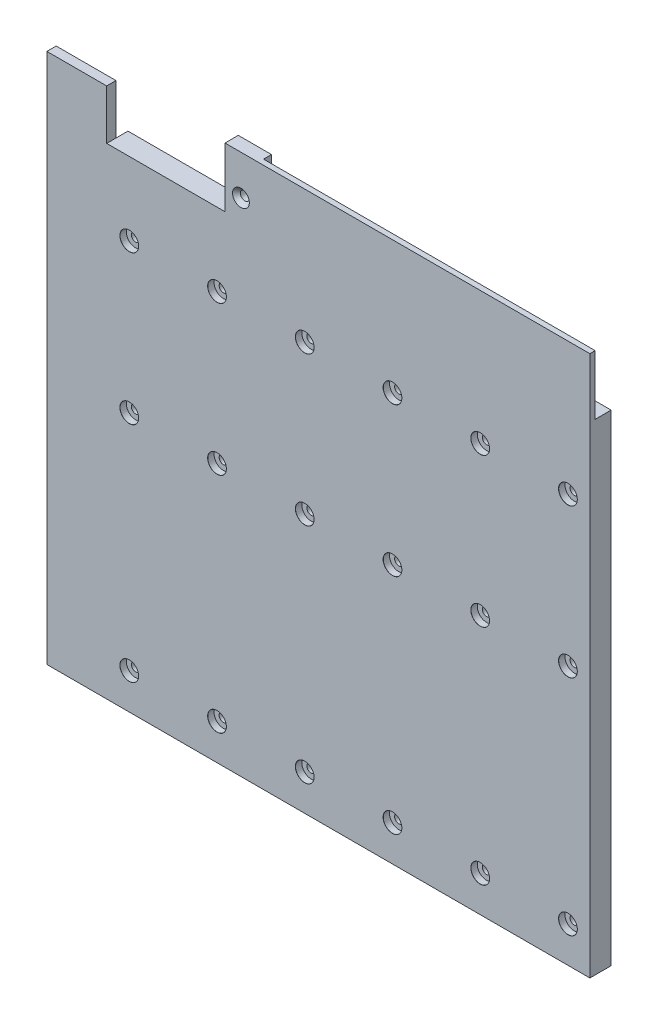
SolidWorks part; units mm, degrees
ref_plane "Plan de face" through (0, 0, 0) normal (0, 0, 1) x (1, 0, 0)
ref_plane "Plan de dessus" through (0, 0, 0) normal (0, 1, 0) x (1, 0, 0)
ref_plane "Plan de droite" through (0, 0, 0) normal (1, 0, 0) x (0, 0, -1)
sketch "Esquisse1" plane through (0, 0, 0) normal (0, 0, 1) x (1, 0, 0)
  line L1 (-204.25, -90.5) -> (204.25, -90.5)
  line L2 (-204.25, -90.5) -> (-204.25, 90.5)
  line L3 (-204.25, 90.5) -> (204.25, 90.5)
  line L4 (204.25, -90.5) -> (204.25, 90.5)
  line L5 (-204.25, -90.5) -> (204.25, 90.5) construction
  line L6 (-204.25, 90.5) -> (204.25, -90.5) construction
  point P0 (0, 0)
  dimension "D1" = 181
  dimension "D2" = 408.5
extrude "Boss.-Extru.1" add sketch "Esquisse1" along normal blind 8 contours L3 L4 L1 L2
hole_wizard "Chambrage pour vis à tête ronde bombée M31" positions "Esquisse2" profile "Esquisse3" counterbore size "M3" standard "Ansi Metric" end condition through all
sketch "Esquisse2" plane through (0, 0, 8) normal (0, 0, 1) x (1, 0, 0)
  point P0 (-173.25, 63)
  point P3 (-173.25, 7)
  point P6 (-173.25, -77)
sketch "Esquisse3" plane through (-173.25, 63, 8) normal (1, 0, 0) x (0, -1, 0)
  line L0 (0, 0) -> (0, 8)
  line L1 (0, 8) -> (1.6, 8)
  line L3 (1.6, 8) -> (1.6, 2.4)
  line L4 (3.5, 2.4) -> (1.6, 2.4)
  line L5 (3.5, 2.4) -> (3.5, 0.025)
  line L6 (3.5, 0.025) -> (3.525, 0)
  line L7 (3.525, 0) -> (0, 0)
  line L8 (-3.5, 0.025) -> (-3.525, 0) construction
  line L11 (0, -6.35) -> (0, 107.95) construction
  dimension "Diamètre du perçage jusqu'au prochain" = 3.2
  dimension "Profondeur du perçage jusqu'au prochain" = 8
  dimension "Diamètre du chambrage" = 7
  dimension "Profondeur du chambrage" = 2.4
  dimension "Diamètre du fraisage entrant" = 7.05
  dimension "Angle du fraisage entrant" = 90
pattern_linear "Répétition linéaire1" count 11 spacing 33 along (1, 0, 0) of "Chambrage pour vis à tête ronde bombée M31"
sketch "Esquisse6" plane through (0, 90.5, 0) normal (0, 1, 0) x (1, 0, 0)
  line L0 (-204.25, 0) -> (204.25, 0) construction
  line L1 (-204.25, 0) -> (-181.75, 0)
  line L2 (-204.25, 0) -> (-204.25, -4.5)
  line L3 (-204.25, -4.5) -> (-181.75, -4.5)
  line L4 (-181.75, 0) -> (-181.75, -4.5)
  line L6 (-204.25, -8) -> (204.25, -8) construction
  line L7 (0, -4.4) -> (0, 4.4) construction
  line L8 (181.75, 0) -> (181.75, -4.5)
  line L9 (204.25, -4.5) -> (181.75, -4.5)
  line L10 (204.25, 0) -> (204.25, -4.5)
  line L11 (204.25, 0) -> (181.75, 0)
  line L12 (-204.25, -8) -> (-204.25, 0) construction
  dimension "D2" = 3.5
  dimension "D3" = 22.5
extrude "Enlèv. mat.-Extru.1" cut sketch "Esquisse6" against normal up to next
sketch "Esquisse7" plane through (0, 0, 8) normal (0, 0, 1) x (1, 0, 0)
  line L1 (-204.25, 90.5) -> (-181.75, 90.5)
  line L2 (-204.25, 90.5) -> (-204.25, 109.225)
  line L3 (-204.25, 109.225) -> (-181.75, 109.225)
  line L4 (-181.75, 90.5) -> (-181.75, 109.225)
  dimension "D1" = 22.5
  dimension "D2" = 18.725
extrude "Boss.-Extru.2" add sketch "Esquisse7" against normal up to vertex
mirror "Symétrie1" about plane through (0, 0, 0) normal (1, 0, 0) of "Boss.-Extru.2"
sketch "Esquisse8" plane through (0, 0, 8) normal (0, 0, 1) x (1, 0, 0)
  line L0 (-181.75, 90.5) -> (181.75, 90.5) construction
  line L1 (-137.25, 90.5) -> (137.25, 90.5)
  line L2 (-137.25, 90.5) -> (-137.25, 112.875)
  line L3 (-137.25, 112.875) -> (137.25, 112.875)
  line L4 (137.25, 90.5) -> (137.25, 112.875)
  line L5 (-137.75, 91) -> (-137.75, 116.55) construction
  line L7 (124.75, 113.375) -> (137.75, 113.375) construction
  line L8 (137.75, 91) -> (137.75, 116.55) construction
  dimension "D1" = 0.5
  dimension "D2" = 0.5
  dimension "D3" = 0.5
extrude "Boss.-Extru.3" add sketch "Esquisse8" against normal blind 5
hole_wizard "Fraisage pour vis à tête fraisée M31" positions "Esquisse9" profile "Esquisse10" countersink size "M3" standard "Ansi Metric" end condition through all
sketch "Esquisse9" plane through (0, 0, 8) normal (0, 0, 1) x (1, 0, 0)
  point P0 (-131.25, 98)
  point P3 (131.25, 98)
sketch "Esquisse10" plane through (-131.25, 98, 8) normal (1, 0, 0) x (0, -1, 0)
  line L0 (0, 0) -> (0, 8)
  line L1 (0, 8) -> (1.7, 8)
  line L2 (1.7, 8) -> (1.7, 1.45)
  line L3 (1.7, 1.45) -> (3.15, 0)
  line L5 (3.15, 0) -> (0, 0)
  line L6 (-1.7, 1.45) -> (-3.15, 0) construction
  line L11 (0, -6.35) -> (0, 107.95) construction
  dimension "Diamètre du perçage jusqu'au prochain" = 3.4
  dimension "Profondeur du perçage jusqu'au prochain" = 8
  dimension "Diamètre du fraisage entrant" = 6.3
  dimension "Angle du fraisage entrant" = 90
ref_plane "Plan1" through (137.25, 112.875, 3) normal (-1, 0, 0) x (0, 0, 1)
sketch "Esquisse12" plane through (0, 0, 3) normal (0, 0, -1) x (-1, 0, 0)
  line L1 (-124.75, 91) -> (-124.75, 113.375) construction
  line L3 (124.75, 91) -> (124.75, 113.375) construction
  line L4 (137.25, 90.5) -> (137.25, 112.875)
  line L5 (137.25, 112.875) -> (-137.25, 112.875)
  line L6 (-137.25, 112.875) -> (-137.25, 90.5)
  line L7 (-137.25, 90.5) -> (137.25, 90.5)
  line L8 (124.75, 90.5) -> (124.75, 112.875)
  line L9 (124.75, 112.875) -> (-124.75, 112.875)
  line L10 (-124.75, 112.875) -> (-124.75, 90.5)
  line L11 (-124.75, 90.5) -> (124.75, 90.5)
  dimension "D1" = 0
extrude "Enlèv. mat.-Extru.2" cut sketch "Esquisse12" against normal blind 3
sketch "Esquisse13" plane through (0, 0, 0) normal (0, 0, -1) x (-1, 0, 0)
  line L0 (181.75, -90.5) -> (-181.75, -90.5) construction
  line L1 (0, -90.5) -> (-204.25, -90.5)
  line L2 (0, -90.5) -> (0, 112.875)
  line L3 (0, 112.875) -> (-204.25, 112.875)
  line L4 (-204.25, -90.5) -> (-204.25, 112.875)
  line L5 (124.75, 112.875) -> (-124.75, 112.875) construction
  line L6 (-204.25, -90.5) -> (-204.25, 109.225) construction
extrude "Enlèv. mat.-Extru.3" cut sketch "Esquisse13" against normal blind 10
